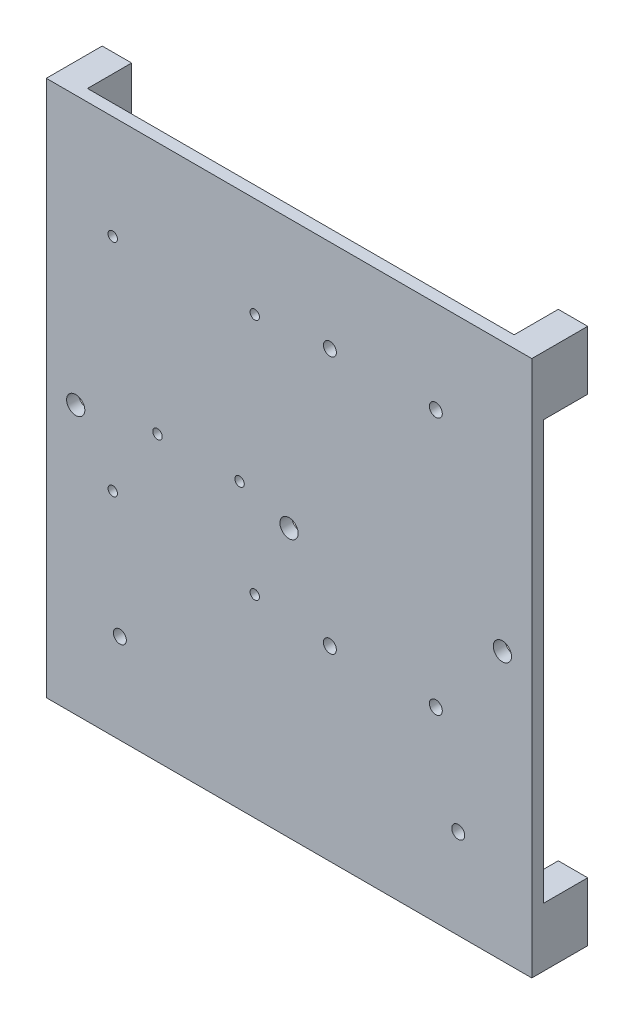
SolidWorks part; units mm, degrees
ref_plane "Front Plane" through (0, 0, 0) normal (0, 0, 1) x (1, 0, 0)
ref_plane "Top Plane" through (0, 0, 0) normal (0, 1, 0) x (1, 0, 0)
ref_plane "Right Plane" through (0, 0, 0) normal (1, 0, 0) x (0, 0, -1)
sketch "Sketch1" plane through (0, 0, 0) normal (0, 0, 1) x (1, 0, 0)
  line L0 (60.5, -15.5) -> (-60.5, -15.5) construction
  line L1 (-82.5, -30.5) -> (82.5, -30.5)
  line L2 (-82.5, -30.5) -> (-82.5, 151.81)
  line L3 (-82.5, 151.81) -> (82.5, 151.81)
  line L4 (82.5, -30.5) -> (82.5, 151.81)
  line L5 (-62.4557, 131.81) -> (-9.1157, 131.81) construction
  line L6 (-62.5, 5.25) -> (-62.5, 13.5) construction
  line L7 (62.5, 13.5) -> (62.5, 5.25) construction
  dimension "D1" = 15
  dimension "D2" = 20
  dimension "D3" = 20
  dimension "D4" = 20
extrude "Boss-Extrude1" add sketch "Sketch1" along normal blind 4
sketch "Sketch2" plane through (0, 0, 0) normal (0, 0, -1) x (-1, 0, 0)
  circle A0 centre (-49.8843, 120.4) radius 2.2
  circle A1 centre (-49.8843, 32.9) radius 2.2
  circle A2 centre (-13.8843, 32.9) radius 2.2
  circle A3 centre (-13.8843, 120.4) radius 2.2
  circle A4 centre (57.5, 0) radius 2.2
  circle A5 centre (-57.5, 0) radius 2.2
  circle A6 centre (11.6557, 35.29) radius 1.6
  circle A7 centre (16.8157, 66) radius 1.6
  circle A8 centre (11.6557, 117.69) radius 1.6
  circle A9 centre (59.9157, 116.57) radius 1.6
  circle A10 centre (44.7157, 66) radius 1.6
  circle A11 centre (59.9157, 41.64) radius 1.6
  dimension "D1" = 4.4
  dimension "D2" = 4.4
  dimension "D3" = 4.4
  dimension "D4" = 4.4
  dimension "D5" = 4.4
  dimension "D6" = 4.4
  dimension "D7" = 3.2
  dimension "D8" = 3.2
  dimension "D9" = 3.2
  dimension "D10" = 3.2
  dimension "D11" = 3.2
  dimension "D12" = 3.2
extrude "Cut-Extrude1" cut sketch "Sketch2" against normal blind 4
sketch "Sketch3" plane through (0, 0, 0) normal (0, 0, -1) x (-1, 0, 0)
  line L1 (-82.5, -30.5) -> (-72.5, -30.5)
  line L2 (-82.5, -30.5) -> (-82.5, -10.5)
  line L3 (-82.5, -10.5) -> (-72.5, -10.5)
  line L4 (-72.5, -30.5) -> (-72.5, -10.5)
  line L5 (-82.5, 151.81) -> (-72.5, 151.81)
  line L6 (-82.5, 151.81) -> (-82.5, 131.81)
  line L7 (-82.5, 131.81) -> (-72.5, 131.81)
  line L8 (-72.5, 151.81) -> (-72.5, 131.81)
  line L9 (82.5, -30.5) -> (72.5, -30.5)
  line L10 (82.5, -30.5) -> (82.5, -10.5)
  line L11 (82.5, -10.5) -> (72.5, -10.5)
  line L12 (72.5, -30.5) -> (72.5, -10.5)
  line L13 (82.5, 151.81) -> (72.5, 151.81)
  line L14 (82.5, 151.81) -> (82.5, 131.81)
  line L15 (82.5, 131.81) -> (72.5, 131.81)
  line L16 (72.5, 151.81) -> (72.5, 131.81)
  dimension "D1" = 10
  dimension "D2" = 20
  dimension "D3" = 10
  dimension "D4" = 20
  dimension "D5" = 10
  dimension "D6" = 20
  dimension "D7" = 10
  dimension "D8" = 20
extrude "Boss-Extrude2" add sketch "Sketch3" along normal blind 15
sketch "Sketch4" plane through (0, 0, 0) normal (0, 0, -1) x (-1, 0, 0)
  line L0 (-82.5, -10.5) -> (-82.5, 131.81) construction
  line L1 (82.5, 131.81) -> (82.5, -10.5) construction
  line L2 (-82.5, 60.655) -> (82.5, 60.655) construction
  circle A0 centre (-72.5, 60.655) radius 3.1
  circle A1 centre (72.5, 60.655) radius 3.1
  circle A2 centre (0, 60.655) radius 3.1
  circle A3 centre (0, 60.655) radius 4.25 construction
  dimension "D1" = 6.2
  dimension "D2" = 6.2
  dimension "D3" = 6.2
  dimension "D6" = 8.5
  dimension "D4" = 10
  dimension "D5" = 10
extrude "Cut-Extrude2" cut sketch "Sketch4" against normal up to next
